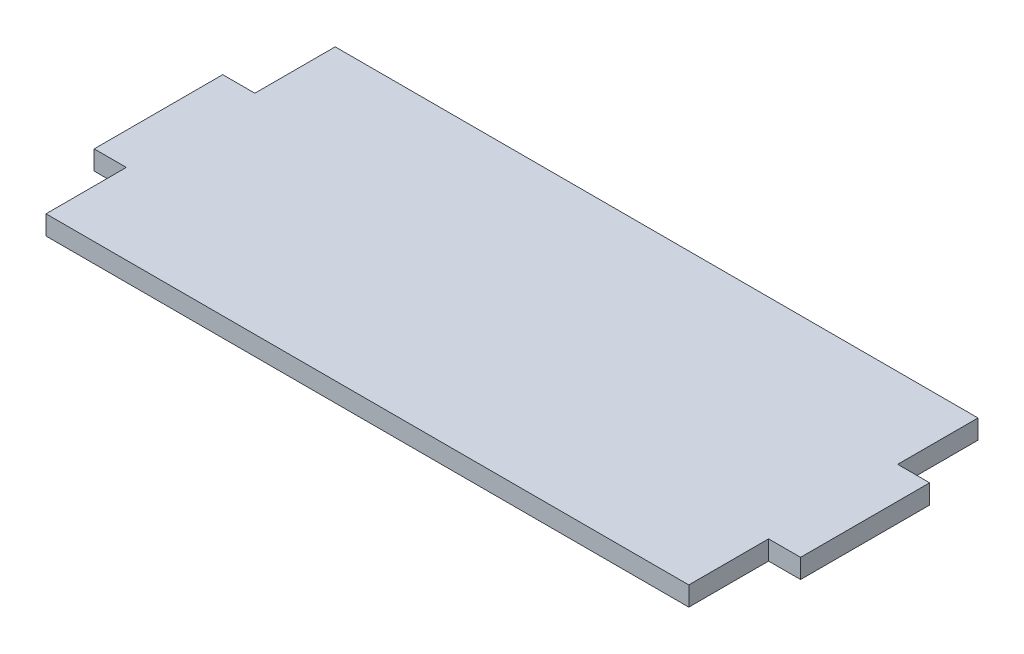
SolidWorks part; units mm, degrees
ref_plane "前视基准面" through (0, 0, 0) normal (0, 0, 1) x (1, 0, 0)
ref_plane "上视基准面" through (0, 0, 0) normal (0, 1, 0) x (1, 0, 0)
ref_plane "右视基准面" through (0, 0, 0) normal (1, 0, 0) x (0, 0, -1)
sketch "草图1" plane through (0, 0, 0) normal (0, 1, 0) x (1, 0, 0)
  line L0 (-50, 22.5) -> (-50, -22.5)
  line L1 (-50, 22.5) -> (50.0233, 22.5)
  line L2 (-50, -22.5) -> (50.0233, -22.5)
  line L3 (50.0233, 22.5) -> (50.0233, -22.5)
  line L4 (50, 10) -> (55, 10)
  line L5 (50, 10) -> (50, -10.0853)
  line L6 (55, 10) -> (55, -10.0853)
  line L7 (50, -10.0853) -> (55, -10.0853)
  line L8 (-55, 10) -> (-55, -10)
  line L9 (-55, 10) -> (-49.7006, 10)
  line L10 (-55, -10) -> (-49.7006, -10)
  line L11 (-49.7006, 10) -> (-49.7006, -10)
  point P0 (50, 22.5)
  point P1 (50, -22.5)
  point P2 (-50, 22.5)
  point P3 (-50, -22.5)
  point P4 (50, 10)
  point P5 (50, -10)
  point P6 (55, 10)
  point P7 (55, -10)
  point P8 (-55, 10)
  point P9 (-55, -10)
  point P10 (-50, 10)
  point P11 (-50, -10)
  point P12 (0, 0)
  point P19 (0, 0)
  point P20 (0, 0)
extrude "凸台-拉伸1" add sketch "草图1" along normal blind 3 contours L8 L10 L0 L9 | L9 L11 L10 L0 L2 L3 L7 L5 L4 L1 | L3 L7 L6 L4
